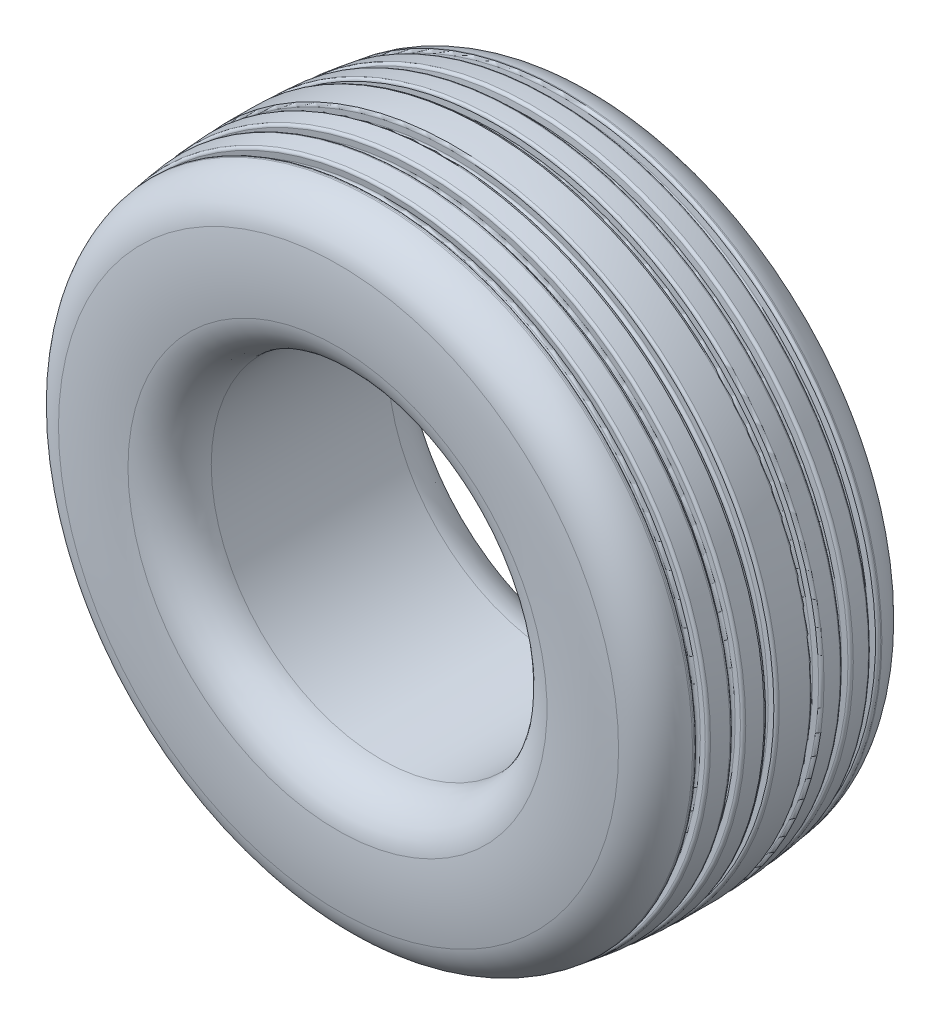
SolidWorks part; units mm, degrees
ref_plane "Plan de face" through (0, 0, 0) normal (0, 0, 1) x (1, 0, 0)
ref_plane "Plan de dessus" through (0, 0, 0) normal (0, 1, 0) x (1, 0, 0)
ref_plane "Plan de droite" through (0, 0, 0) normal (1, 0, 0) x (0, 0, -1)
sketch "Esquisse1" plane through (0, 0, 0) normal (1, 0, 0) x (0, 0, -1)
  line L0 (-600, 0) -> (600, 0) construction
  line L1 (0, 0) -> (0, 700) construction
  line L2 (-280, 382.94) -> (280, 382.94)
  line L3 (-280, 700) -> (280, 700) construction
  line L4 (-280, 382.94) -> (-280, 700) construction
  line L5 (280, 382.94) -> (280, 700) construction
  arc A0 (-280, 700) -> (280, 700) centre (0, -591.6667) cw
  arc A1 (-280, 700) -> (-280, 382.94) centre (277.9142, 541.47) ccw
  arc A2 (280, 700) -> (280, 382.94) centre (-277.9142, 541.47) cw
  point P10 (0, 730)
  point P12 (-280, 700)
  point P13 (0, 0)
  dimension "D7" = 580
  dimension "D1" = 560
  dimension "D2" = 382.94
  dimension "D3" = 700
  dimension "D4" = 700
  dimension "D6" = 30
revolve "Révolution1" add sketch "Esquisse1" angle 360 about L0
sketch "Esquisse4" plane through (0, 0, 0) normal (1, 0, 0) x (0, 0, -1)
  line L0 (0, 0) -> (0, 730) construction
  line L1 (-40, 704.3829) -> (-40.7712, 729.371)
  line L2 (-60, 703.6111) -> (-61.1568, 728.5843)
  line L3 (-110, 700.3258) -> (-112.1208, 725.2356)
  line L4 (-130, 698.4668) -> (-132.5064, 723.3409)
  line L5 (-180, 692.4457) -> (-183.4704, 717.2036)
  line L6 (-200, 689.483) -> (-203.856, 714.1838)
  line L7 (-274.7037, 0) -> (274.7037, 0) construction
  arc A5 (-180, 692.4457) -> (-200, 689.483) centre (0, -591.6667) ccw
  arc A6 (-183.4704, 717.2036) -> (-203.856, 714.1838) centre (0, -591.6667) ccw
  arc A7 (-110, 700.3258) -> (-130, 698.4668) centre (0, -591.6667) ccw
  arc A8 (-112.1208, 725.2356) -> (-132.5064, 723.3409) centre (0, -591.6667) ccw
  arc A9 (-40, 704.3829) -> (-60, 703.6111) centre (0, -591.6667) ccw
  arc A10 (-40.7712, 729.371) -> (-61.1568, 728.5843) centre (0, -591.6667) ccw
  dimension "D2" = 40
  dimension "D3" = 20
  dimension "D4" = 50
  dimension "D5" = 20
  dimension "D6" = 50
  dimension "D7" = 20
revolve "Enlèvement de matière-Révolution1" cut sketch "Esquisse4" angle 360 about L7
fillet "Congé1" radius 6 12 edges at (725.2356, 0, 112.1208) (729.371, 0, 40.7712) (723.3409, 0, 132.5064) (717.2036, 0, 183.4704) (714.1838, 0, 203.856) (704.3829, 0, 40) (703.6111, 0, 60) (728.5843, 0, 61.1568) (700.3258, 0, 110) (698.4668, 0, 130) (692.4457, 0, 180) (689.483, 0, 200)
mirror "Symétrie1" about plane through (0, 0, 0) normal (0, 0, 1) of "Enlèvement de matière-Révolution1", "Congé1"
fillet "Congé3" radius 100 4 edges at (700, 0, -280) (700, 0, 280) (382.94, 0, 280) (382.94, 0, -280)
